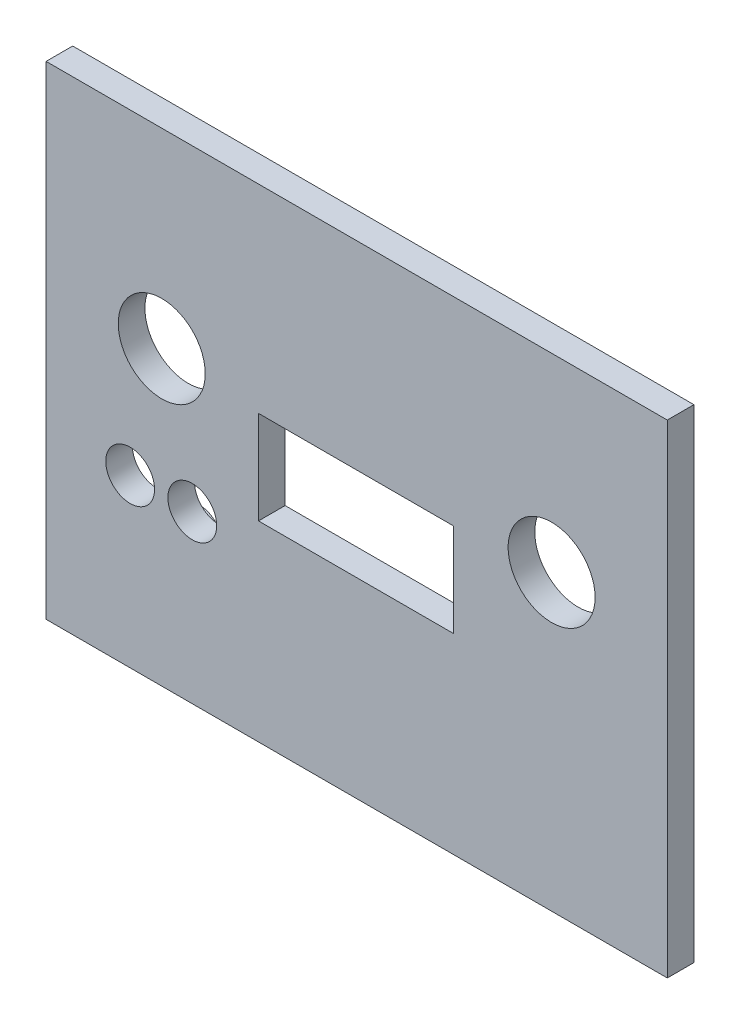
SolidWorks part; units mm, degrees
ref_plane "Płaszczyzna przednia" through (0, 0, 0) normal (0, 0, 1) x (1, 0, 0)
ref_plane "Płaszczyzna górna" through (0, 0, 0) normal (0, 1, 0) x (1, 0, 0)
ref_plane "Płaszczyzna prawa" through (0, 0, 0) normal (1, 0, 0) x (0, 0, -1)
sketch "Szkic1" plane through (0, 0, 0) normal (0, 0, 1) x (1, 0, 0)
  line L1 (-5, 49.45) -> (65, 49.45)
  line L2 (-5, 49.45) -> (-5, -5)
  line L3 (-5, -5) -> (65, -5)
  line L4 (65, 49.45) -> (65, -5)
  line L5 (18.934, 27.07) -> (40.934, 27.07)
  line L6 (18.934, 27.07) -> (18.934, 16.57)
  line L7 (18.934, 16.57) -> (40.934, 16.57)
  line L8 (40.934, 27.07) -> (40.934, 16.57)
  circle A0 centre (8.0336, 27.9335) radius 4.9012
  circle A1 centre (51.9664, 28.0665) radius 4.9012
  circle A2 centre (4.475, 13.7901) radius 2.75
  circle A3 centre (11.475, 13.75) radius 2.75
  circle A4 centre (56, 40.5) radius 2.5
  circle A5 centre (4, 40.5) radius 2.5
  circle A6 centre (4, 4) radius 2.5
  circle A7 centre (56, 4) radius 2.5
  circle A8 centre (18.284, 8.17) radius 0.8
  circle A9 centre (41.584, 8.17) radius 0.8
  circle A10 centre (18.284, 31.97) radius 0.8
  circle A11 centre (41.584, 31.97) radius 0.8
sketch "Szkic2" plane through (0, 0, 0) normal (0, 0, 1) x (1, 0, 0)
  line L1 (-5, 49.45) -> (65, 49.45)
  line L2 (-5, 49.45) -> (-5, -5)
  line L3 (-5, -5) -> (65, -5)
  line L4 (65, 49.45) -> (65, -5)
  line L5 (18.934, 27.07) -> (40.934, 27.07)
  line L6 (18.934, 27.07) -> (18.934, 16.57)
  line L7 (18.934, 16.57) -> (40.934, 16.57)
  line L8 (40.934, 27.07) -> (40.934, 16.57)
  circle A0 centre (8.0336, 27.9335) radius 4.9012
  circle A1 centre (51.9664, 28.0665) radius 4.9012
  circle A2 centre (4.475, 13.7901) radius 2.75
  circle A3 centre (11.475, 13.75) radius 2.75
  circle A4 centre (56, 40.5) radius 2.5
  circle A5 centre (4, 40.5) radius 2.5
  circle A6 centre (4, 4) radius 2.5
  circle A7 centre (56, 4) radius 2.5
  circle A8 centre (18.284, 8.17) radius 0.8
  circle A9 centre (41.584, 8.17) radius 0.8
  circle A10 centre (18.284, 31.97) radius 0.8
  circle A11 centre (41.584, 31.97) radius 0.8
extrude "Dodanie-wyciągnięcie2" add sketch "Szkic1" along normal blind 3 contours A0 | A1 | A2 | L2 L3 L4 L1 | L6 L7 L8 L5 | A3
sketch "Szkic3" plane through (0, 0, 0) normal (0, 0, -1) x (-1, 0, 0)
  circle A0 centre (-56, 40.5) radius 2.5
  circle A1 centre (-4, 40.5) radius 2.5
  circle A2 centre (-56, 4) radius 2.5
  circle A3 centre (-4, 4) radius 2.5
extrude "Dodanie-wyciągnięcie3" add sketch "Szkic3" along normal blind 5.3
sketch "Szkic5" plane through (0, 0, -5.3) normal (0, 0, -1) x (-1, 0, 0)
  circle A0 centre (-56, 40.5) radius 1.25
  circle A1 centre (-4, 40.5) radius 1.25
  circle A2 centre (-56, 4) radius 1.25
  circle A3 centre (-4, 4) radius 1.25
extrude "Wytnij-wyciągnięcie1" cut sketch "Szkic5" against normal blind 5
sketch "Szkic6" plane through (0, 0, 0) normal (0, 0, -1) x (-1, 0, 0)
  circle A0 centre (-41.584, 31.97) radius 0.8
  circle A1 centre (-18.284, 31.97) radius 0.8
  circle A2 centre (-41.584, 8.17) radius 0.8
  circle A3 centre (-18.284, 8.17) radius 0.8
extrude "Dodanie-wyciągnięcie4" add sketch "Szkic6" along normal blind 5
